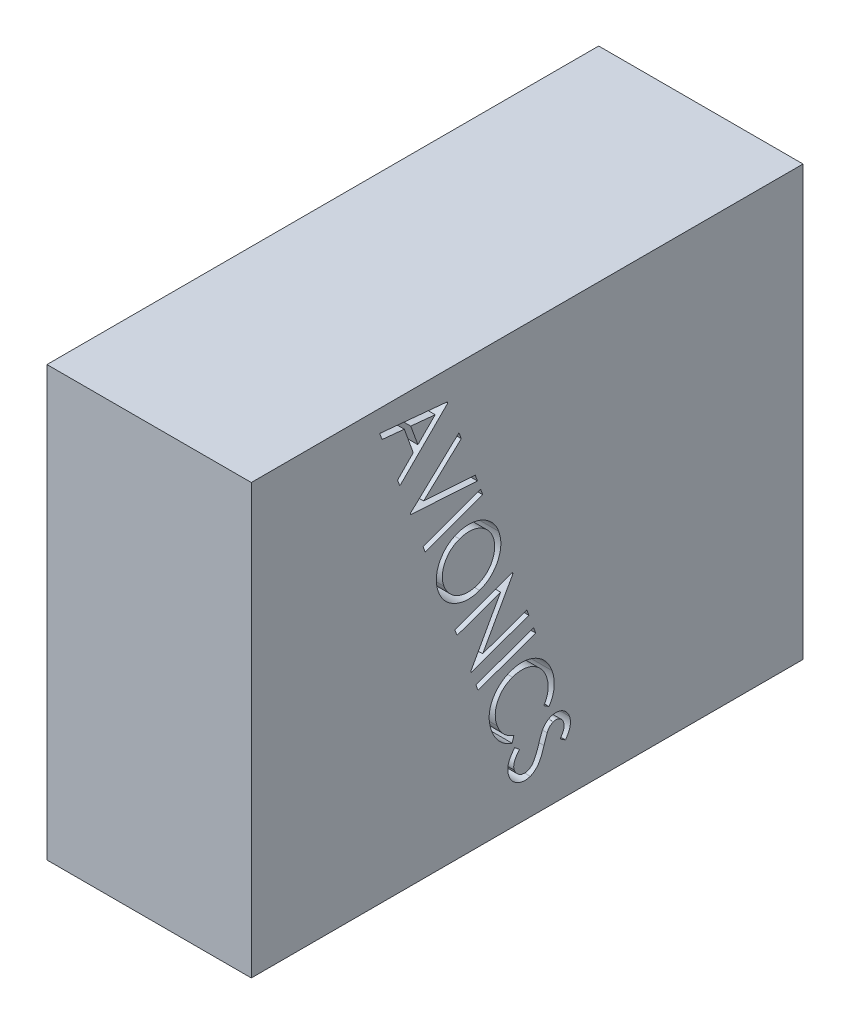
SolidWorks part; units mm, degrees
ref_plane "Front Plane" through (0, 0, 0) normal (0, 0, 1) x (1, 0, 0)
ref_plane "Top Plane" through (0, 0, 0) normal (0, 1, 0) x (1, 0, 0)
ref_plane "Right Plane" through (0, 0, 0) normal (1, 0, 0) x (0, 0, -1)
sketch "Sketch1" plane through (0, 0, 0) normal (0, 1, 0) x (1, 0, 0)
  line L1 (0, 0) -> (25.4, 0)
  line L2 (0, 0) -> (0, -68.58)
  line L3 (0, -68.58) -> (25.4, -68.58)
  line L4 (25.4, 0) -> (25.4, -68.58)
  dimension "D1" = 25.4
  dimension "D2" = 68.58
extrude "Boss-Extrude1" add sketch "Sketch1" along normal blind 53.34
sketch "Sketch2" plane through (25.4, 0, 0) normal (1, 0, 0) x (0, 0, -1)
  line L0 (-53.5922, 53.34) -> (-34.29, 0) construction
  line L1 (-68.58, 53.34) -> (0, 53.34) construction
  line L2 (-68.58, 0) -> (0, 0) construction
  text T0 "AVIONICS" font "Century Gothic" height 7.62
  point P7 (0, 0)
extrude "Cut-Extrude1" cut sketch "Sketch2" against normal blind 12.7
